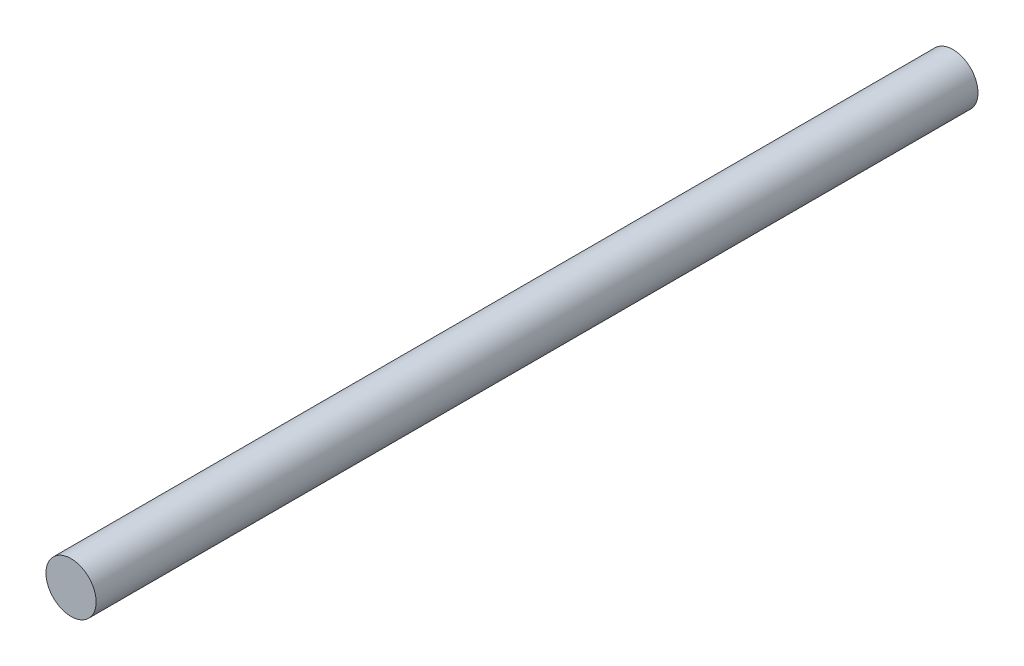
SolidWorks part; units mm, degrees
ref_plane "前视基准面" through (0, 0, 0) normal (0, 0, 1) x (1, 0, 0)
ref_plane "上视基准面" through (0, 0, 0) normal (0, 1, 0) x (1, 0, 0)
ref_plane "右视基准面" through (0, 0, 0) normal (1, 0, 0) x (0, 0, -1)
other "Configuration Table"
sketch "草图1" plane through (0, 0, 0) normal (0, 0, 1) x (1, 0, 0)
  circle A0 centre (0, 0) radius 1.5
extrude "外形" add sketch "草图1" along normal blind 52.75 from offset 0
